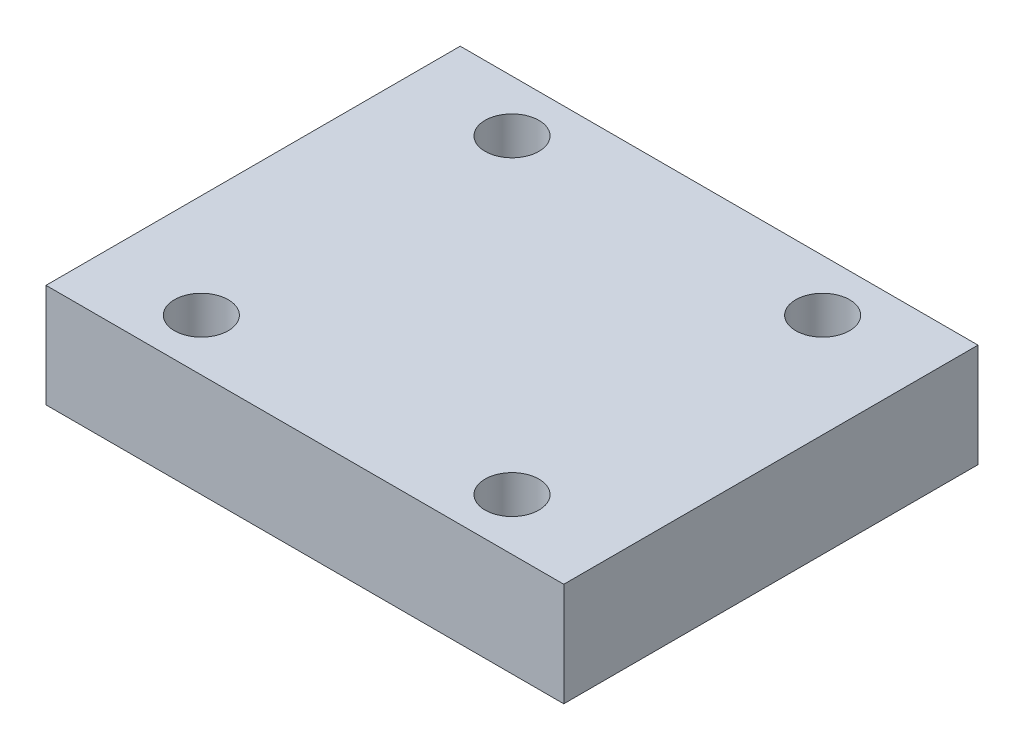
SolidWorks part; units mm, degrees
ref_plane "前视基准面" through (0, 0, 0) normal (0, 0, 1) x (1, 0, 0)
ref_plane "上视基准面" through (0, 0, 0) normal (0, 1, 0) x (1, 0, 0)
ref_plane "右视基准面" through (0, 0, 0) normal (1, 0, 0) x (0, 0, -1)
other "Configuration Table"
sketch "草图1" plane through (0, 0, 0) normal (0, 1, 0) x (1, 0, 0)
  line L0 (0, 0) -> (-7.9884, 0) construction
  line L1 (-25, -20) -> (25, -20)
  line L2 (-25, -20) -> (-25, 20)
  line L3 (-25, 20) -> (25, 20)
  line L4 (25, -20) -> (25, 20)
  line L5 (-25, -20) -> (25, 20) construction
  line L6 (-25, 20) -> (25, -20) construction
  line L7 (0, 0) -> (0, 19.3758) construction
  circle A0 centre (-15, 15) radius 2.6
  circle A1 centre (-15, -15) radius 2.6
  circle A2 centre (15, -15) radius 2.6
  circle A3 centre (15, 15) radius 2.6
  point P0 (0, 0)
  dimension "D3" = 5.2
  dimension "D1" = 50
  dimension "D2" = 40
  dimension "D4" = 30
  dimension "D5" = 30
extrude "凸台-拉伸1" add sketch "草图1" along normal blind 10
